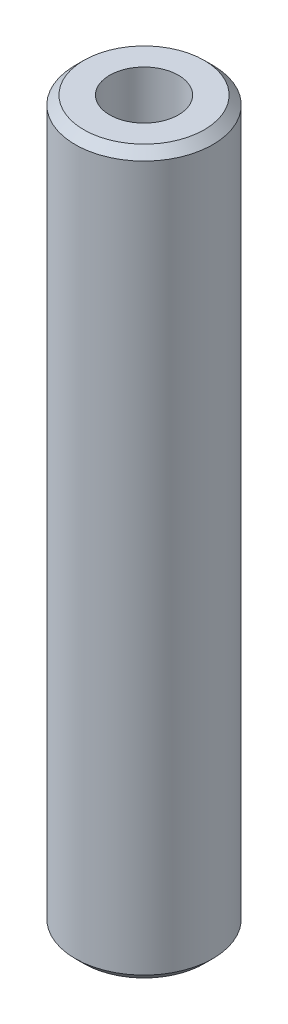
SolidWorks part; units mm, degrees
ref_plane "Front Plane" through (0, 0, 0) normal (0, 0, 1) x (1, 0, 0)
ref_plane "Top Plane" through (0, 0, 0) normal (0, 1, 0) x (1, 0, 0)
ref_plane "Right Plane" through (0, 0, 0) normal (1, 0, 0) x (0, 0, -1)
sketch "Sketch1" plane through (0, 0, 0) normal (0, 1, 0) x (1, 0, 0)
  circle A0 centre (0, 0) radius 2
  circle A1 centre (0, 0) radius 4
  dimension "D1" = 4
  dimension "D2" = 2
extrude "Boss-Extrude1" add sketch "Sketch1" along normal blind 42
chamfer "Chamfer1" distance 0.5 angle 45 2 edges at (0, 0, 4) (0, 42, 4)
